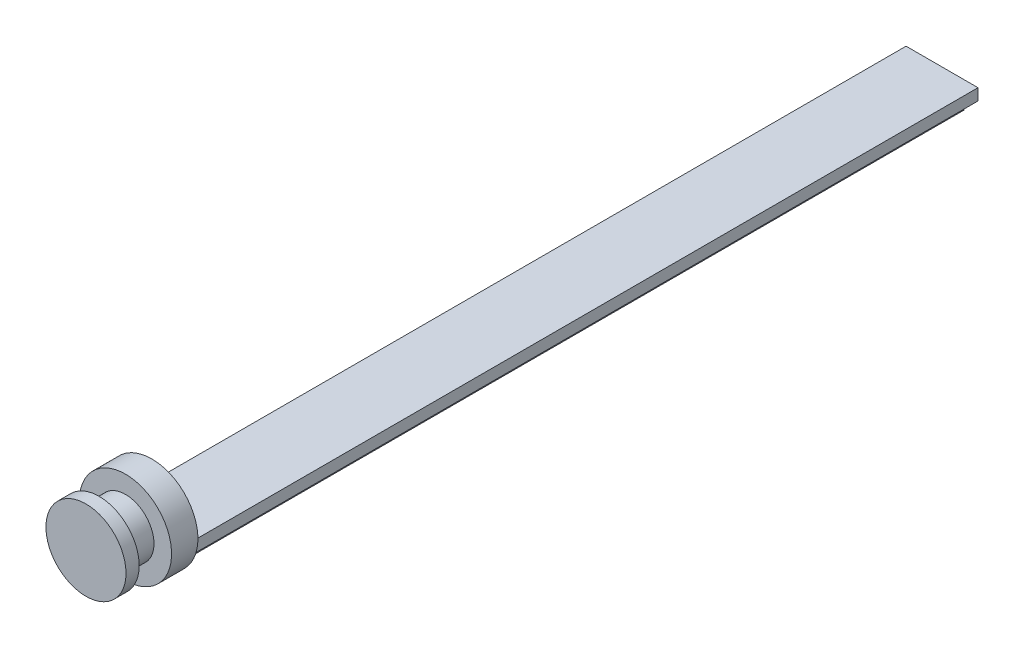
SolidWorks part; units mm, degrees
ref_plane "Alzado" through (0, 0, 0) normal (0, 0, 1) x (1, 0, 0)
ref_plane "Planta" through (0, 0, 0) normal (0, 1, 0) x (1, 0, 0)
ref_plane "Vista lateral" through (0, 0, 0) normal (1, 0, 0) x (0, 0, -1)
sketch "Croquis1" plane through (0, 0, 0) normal (0, 0, 1) x (1, 0, 0)
  circle A0 centre (0, 0) radius 4.56
  dimension "D1" = 9.12
extrude "Saliente-Extruir4" add sketch "Croquis1" along normal blind 1.5
sketch "Croquis4" plane through (0, 0, 0) normal (0, 0, -1) x (-1, 0, 0)
  circle A0 centre (0, 0) radius 3.25
  dimension "D1" = 6.5
extrude "Saliente-Extruir5" add sketch "Croquis4" along normal blind 3
sketch "Croquis5" plane through (0, 0, -3) normal (0, 0, -1) x (-1, 0, 0)
  circle A0 centre (0, 0) radius 5.25
  dimension "D1" = 10.5
extrude "Saliente-Extruir6" add sketch "Croquis5" along normal blind 3 contours A0
sketch "Croquis6" plane through (0, 0, -6) normal (0, 0, -1) x (-1, 0, 0)
  line L0 (0, 5.25) -> (0, -5.25) construction
  line L1 (-4.0961, -1.0889) -> (4.0961, -1.0889)
  line L2 (4.0961, -1.0889) -> (4.0961, -2.4016)
  line L3 (4.0961, -2.4016) -> (-4.0961, -2.4016)
  line L4 (-4.0961, -2.4016) -> (-4.0961, -1.0889)
  line L5 (-2.5, -2.4016) -> (2.5, -2.4016)
  line L6 (2.5, -2.4016) -> (2.5, -4.1022)
  line L7 (2.5, -4.1022) -> (-2.5, -4.1022)
  line L8 (-2.5, -4.1022) -> (-2.5, -2.4016)
  circle A0 centre (0, 0) radius 5.25 construction
  point P8 (0, -1.0889)
  point P13 (0, -2.4016)
  dimension "D1" = 5
extrude "Saliente-Extruir7" add sketch "Croquis6" along normal blind 90 contours L0 L1 L4 L3 L5 | L1 L0 L3 L2 | L3 L0 L7 L6 | L0 L5 L8 L7
